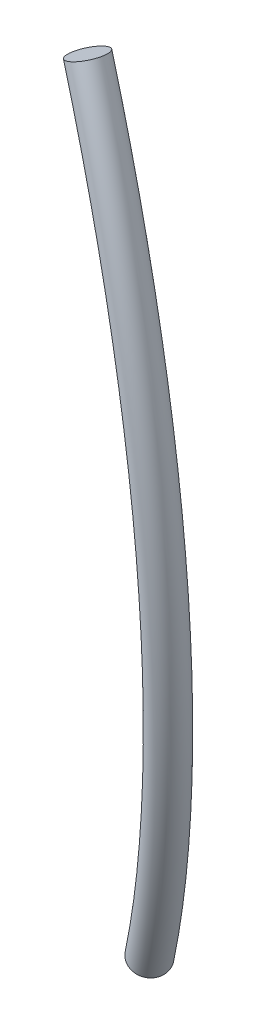
SolidWorks part; units mm, degrees
ref_plane "Front" through (0, 0, 0) normal (0, 0, 1) x (1, 0, 0)
ref_plane "Top" through (0, 0, 0) normal (0, 1, 0) x (1, 0, 0)
ref_plane "Right" through (0, 0, 0) normal (1, 0, 0) x (0, 0, -1)
ref_plane "Plane1" through (7284.2402, 1208.7442, -16012.3295) normal (-0.4131, -0.0686, 0.9081) x (0.9104, -0.0556, 0.41)
sketch "Sketch2" plane through (7284.2402, 1208.7442, -16012.3295) normal (-0.4131, -0.0686, 0.9081) x (0.9104, -0.0556, 0.41)
  line L0 (-139.2647, -3617.1068) -> (3.6955, -3278.1032) construction
  line L2 (-201.2061, -1252.3541) -> (-379.5823, -884.4536) construction
  arc A0 (-139.2647, -3617.1068) -> (-201.2061, -1252.3541) centre (-2780.8933, -2503.1129) ccw
  point P6 (-67.0061, -3427.2341)
  dimension "D3" = 203.2
  dimension "D1" = 2438.4
  dimension "D2" = 2743.2
sketch "Sketch3" plane through (-1268.1198, -3035.4363, -806.0261) normal (0.3744, 0.8962, 0.238) x (-0.9273, 0.3619, 0.0961)
  circle A0 centre (-8999.0556, -15217.23) radius 50.8
  circle A1 centre (-8999.0556, -15217.23) radius 50.8 construction
sweep "Sweep1" add profiles "Sketch3" path "Sketch2"
